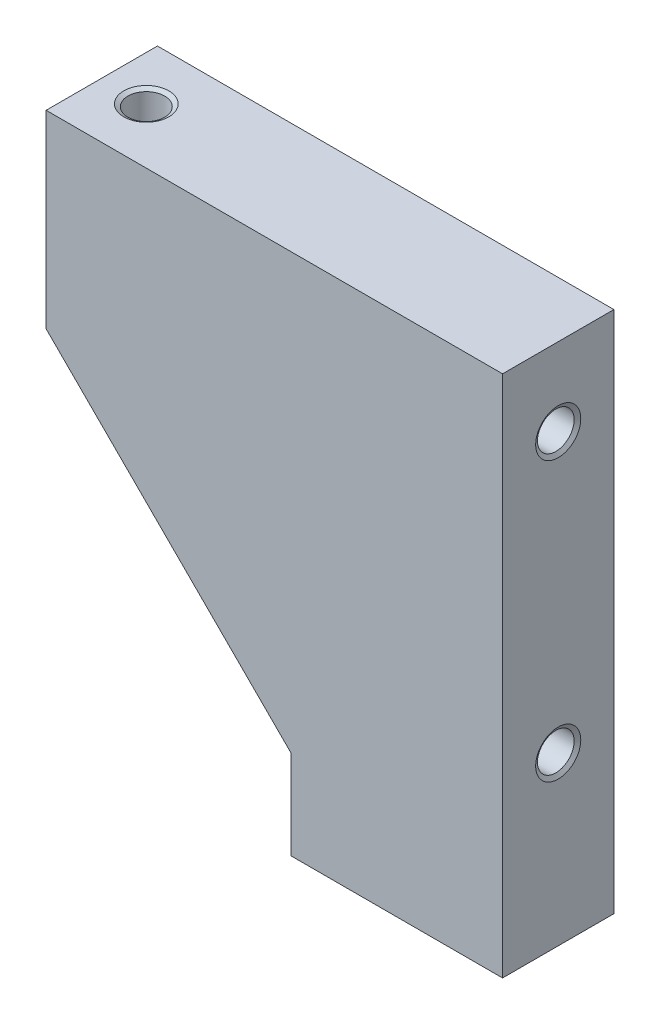
SolidWorks part; units mm, degrees
material "Д16Т ГОСТ 4784-74"
ref_plane "Спереди" through (0, 0, 0) normal (0, 0, 1) x (1, 0, 0)
ref_plane "Сверху" through (0, 0, 0) normal (0, 1, 0) x (1, 0, 0)
ref_plane "Справа" through (0, 0, 0) normal (1, 0, 0) x (0, 0, -1)
sketch "Эскиз1" plane through (0, 0, 0) normal (0, 0, 1) x (1, 0, 0)
  line L0 (0, 0) -> (0, 8)
  line L1 (0, 8) -> (-22, 30)
  line L2 (-22, 30) -> (-22, 47)
  line L3 (-22, 47) -> (19, 47)
  line L4 (19, 47) -> (19, 0)
  line L5 (19, 0) -> (0, 0)
  dimension "D1" = 47
  dimension "D2" = 19
  dimension "D3" = 41
  dimension "D4" = 135
  dimension "D5" = 8
extrude "Бобышка-Вытянуть1" add sketch "Эскиз1" along normal blind 10
hole_wizard "Отверстие обработанное метчиком M41" positions "Эскиз3" profile "Эскиз2" tap size "M4" standard "DIN"
sketch "Эскиз3" plane through (19, 0, 0) normal (1, 0, 0) x (0, 0, -1)
  line L0 (-5, 0) -> (-5, 15)
  line L1 (-10, 0) -> (0, 0) construction
  line L2 (-5, 15) -> (-5, 40)
  point P0 (-5, 40)
  point P1 (-5, 15)
  dimension "D1" = 25
  dimension "D2" = 15
sketch "Эскиз2" plane through (19, 40, 5) normal (0, 1, 0) x (0, 0, -1)
  line L0 (0, 0) -> (0, 12.4914)
  line L1 (0, 12.4914) -> (1.65, 11.5)
  line L2 (1.65, 11.5) -> (1.65, 0.2165)
  line L3 (1.65, 0.2165) -> (2.025, 0)
  line L5 (2.025, 0) -> (0, 0)
  line L6 (-1.65, 0.2165) -> (-2.025, 0) construction
  line L10 (0, 12.4914) -> (-1.65, 11.5) construction
  line L11 (0, -6.35) -> (0, 107.95) construction
  dimension "Диаметр сверла" = 3.3
  dimension "Глубина сверла" = 11.5
  dimension "Диаметр передней зенковки" = 4.05
  dimension "Угол передней зенковки" = 120
  dimension "Угол заточки сверла" = 118
cosmetic thread "Отверстие резьбы1" parameters "D1"=8, "D2"=4
cosmetic thread "Отверстие резьбы2" parameters "D1"=8, "D2"=4
hole_wizard "Отверстие обработанное метчиком M42" positions "Эскиз5" profile "Эскиз4" tap size "M4" standard "DIN"
sketch "Эскиз5" plane through (-22, 0, 0) normal (-1, 0, 0) x (0, 0, 1)
  line L0 (10, 47) -> (0, 47) construction
  line L1 (10, 47) -> (10, 30) construction
  point P0 (5, 37)
  dimension "D1" = 10
  dimension "D2" = 5
sketch "Эскиз4" plane through (-22, 37, 5) normal (0, 1, 0) x (0, 0, 1)
  line L0 (0, 0) -> (0, 12.4914)
  line L1 (0, 12.4914) -> (1.65, 11.5)
  line L2 (1.65, 11.5) -> (1.65, 0.2165)
  line L3 (1.65, 0.2165) -> (2.025, 0)
  line L5 (2.025, 0) -> (0, 0)
  line L6 (-1.65, 0.2165) -> (-2.025, 0) construction
  line L10 (0, 12.4914) -> (-1.65, 11.5) construction
  line L11 (0, -6.35) -> (0, 107.95) construction
  dimension "Диаметр сверла" = 3.3
  dimension "Глубина сверла" = 11.5
  dimension "Диаметр передней зенковки" = 4.05
  dimension "Угол передней зенковки" = 120
  dimension "Угол заточки сверла" = 118
cosmetic thread "Отверстие резьбы3" parameters "D1"=8, "D2"=4
hole_wizard "Отверстие обработанное метчиком M43" positions "Эскиз7" profile "Эскиз6" tap size "M4" standard "DIN"
sketch "Эскиз7" plane through (0, 47, 0) normal (0, 1, 0) x (-1, 0, 0)
  line L0 (22, 10) -> (22, 0) construction
  line L1 (-19, 10) -> (22, 10) construction
  point P0 (18, 5)
  dimension "D1" = 4
  dimension "D2" = 5
sketch "Эскиз6" plane through (-18, 47, 5) normal (1, 0, 0) x (0, 0, 1)
  line L0 (0, 0) -> (0, 6.9914)
  line L1 (0, 6.9914) -> (1.65, 6)
  line L2 (1.65, 6) -> (1.65, 0.2165)
  line L3 (1.65, 0.2165) -> (2.025, 0)
  line L5 (2.025, 0) -> (0, 0)
  line L6 (-1.65, 0.2165) -> (-2.025, 0) construction
  line L10 (0, 6.9914) -> (-1.65, 6) construction
  line L11 (0, -6.35) -> (0, 107.95) construction
  dimension "Диаметр сверла" = 3.3
  dimension "Глубина сверла" = 6
  dimension "Диаметр передней зенковки" = 4.05
  dimension "Угол передней зенковки" = 120
  dimension "Угол заточки сверла" = 118
cosmetic thread "Отверстие резьбы4" parameters "D1"=6, "D2"=4
